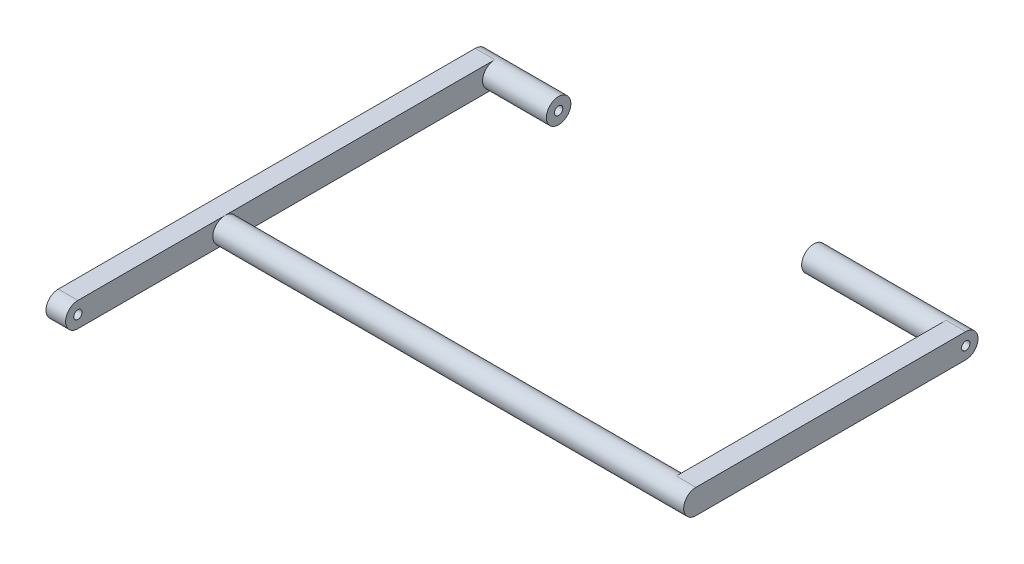
SolidWorks part; units mm, degrees
ref_plane "Plano frontal" through (0, 0, 0) normal (0, 0, 1) x (1, 0, 0)
ref_plane "Plano superior" through (0, 0, 0) normal (0, 1, 0) x (1, 0, 0)
ref_plane "Plano direito" through (0, 0, 0) normal (1, 0, 0) x (0, 0, -1)
sketch "Esboço1" plane through (0, 0, 0) normal (1, 0, 0) x (0, 0, -1)
  line L0 (-27.5, 0) -> (27.5, 0) construction
  line L1 (-27.5, 2.5) -> (27.5, 2.5)
  line L2 (-27.5, -2.5) -> (27.5, -2.5)
  arc A0 (-27.5, 2.5) -> (-27.5, -2.5) centre (-27.5, 0) ccw
  arc A1 (27.5, -2.5) -> (27.5, 2.5) centre (27.5, 0) ccw
  point P2 (0, 0)
  dimension "D1" = 5
  dimension "D2" = 55
extrude "Ressalto-extrusão1" add sketch "Esboço1" along normal blind 4
sketch "Esboço2" plane through (0, 0, 0) normal (-1, 0, 0) x (0, 0, 1)
  circle A0 centre (-27.5, 0) radius 2.5
  arc A1 (-27.5, 2.5) -> (-27.5, -2.5) centre (-27.5, 0) ccw construction
extrude "Ressalto-extrusão2" add sketch "Esboço2" along normal blind 26.96
sketch "Esboço5" plane through (0, 0, 0) normal (-1, 0, 0) x (0, 0, 1)
  circle A0 centre (27.5, 0) radius 2.5
  arc A1 (27.5, -2.5) -> (27.5, 2.5) centre (27.5, 0) ccw construction
extrude "Ressalto-extrusão3" add sketch "Esboço5" along normal blind 92
sketch "Esboço6" plane through (-92, 0, 0) normal (-1, 0, 0) x (0, 0, 1)
  line L0 (27.5, 0) -> (-27.5, 0) construction
  line L1 (27.5, -2.5) -> (-27.5, -2.5)
  line L2 (27.5, 2.5) -> (-27.5, 2.5)
  arc A0 (27.5, -2.5) -> (27.5, 2.5) centre (27.5, 0) ccw
  arc A1 (-27.5, 2.5) -> (-27.5, -2.5) centre (-27.5, 0) ccw
  circle A2 centre (27.5, 0) radius 2.5 construction
  circle A3 centre (-27.5, 0) radius 2.5 construction
  point P2 (0, 0)
extrude "Ressalto-extrusão4" add sketch "Esboço6" along normal blind 4
sketch "Esboço7" plane through (-92, 0, 0) normal (1, 0, 0) x (0, 0, -1)
  circle A0 centre (27.5, 0) radius 2.5
  arc A1 (27.5, -2.5) -> (27.5, 2.5) centre (27.5, 0) ccw construction
extrude "Ressalto-extrusão5" add sketch "Esboço7" along normal blind 13
sketch "Esboço8" plane through (-92, 0, 0) normal (1, 0, 0) x (0, 0, -1)
  line L0 (-27.5, 0) -> (-57.5, 0) construction
  line L1 (-27.5, -2.5) -> (-57.5, -2.5)
  line L2 (-27.5, 2.5) -> (-57.5, 2.5)
  arc A0 (-27.5, -2.5) -> (-27.5, 2.5) centre (-27.5, 0) ccw
  arc A1 (-57.5, 2.5) -> (-57.5, -2.5) centre (-57.5, 0) ccw
  arc A2 (-27.5, 2.5) -> (-27.5, -2.5) centre (-27.5, 0) ccw construction
  point P2 (-42.5, 0)
  dimension "D1" = 30
extrude "Ressalto-extrusão6" add sketch "Esboço8" against normal up to surface (4 mm away) up to face at (-96, 0, 0)
sketch "Esboço3" plane through (-26.96, 0, 0) normal (-1, 0, 0) x (0, 0, 1)
  circle A0 centre (-27.5, 0) radius 0.85
  circle A1 centre (-27.5, 0) radius 2.5 construction
  dimension "D1" = 1.7
extrude "Corte-extrusão1" cut sketch "Esboço3" against normal through all both and the other way through all
sketch "Esboço4" plane through (-96, 0, 0) normal (-1, 0, 0) x (0, 0, 1)
  circle A0 centre (57.5, 0) radius 0.85
  arc A2 (57.5, -2.5) -> (57.5, 2.5) centre (57.5, 0) ccw construction
  dimension "D1" = 1.7
extrude "Corte-extrusão2" cut sketch "Esboço4" against normal through all both and the other way through all
